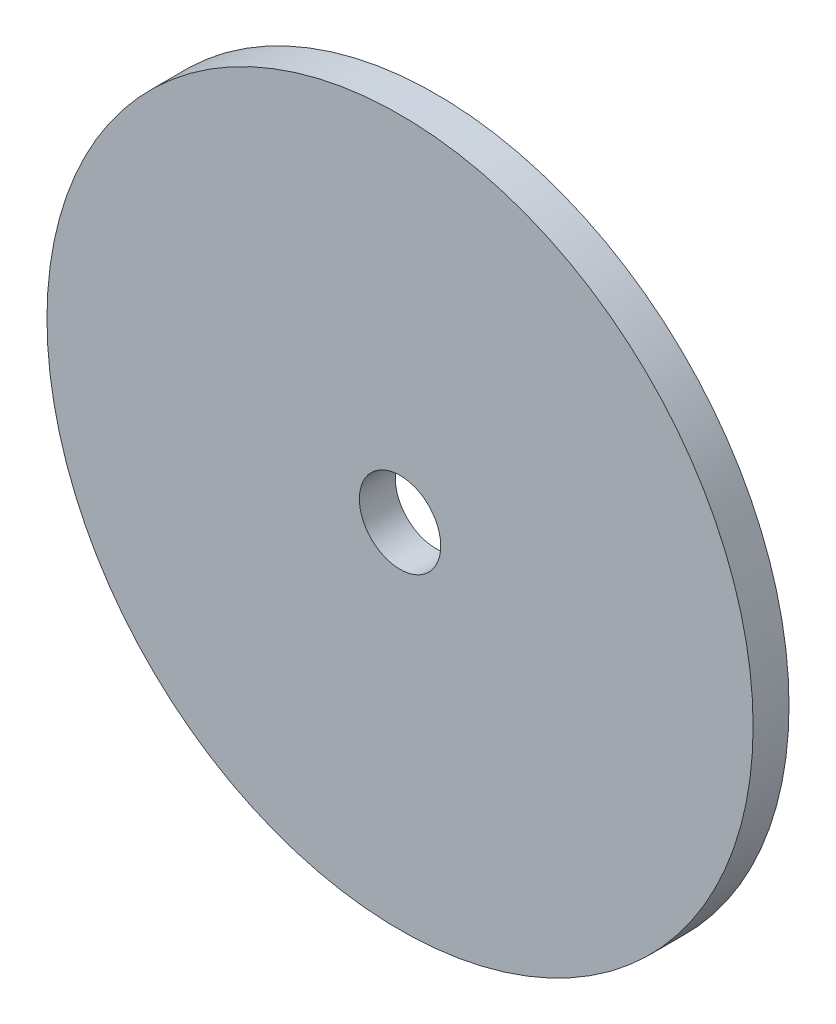
SolidWorks part; units mm, degrees
material "Acrylic (Medium-high impact)"
ref_plane "Front Plane" through (0, 0, 0) normal (0, 0, 1) x (1, 0, 0)
ref_plane "Top Plane" through (0, 0, 0) normal (0, 1, 0) x (1, 0, 0)
ref_plane "Right Plane" through (0, 0, 0) normal (1, 0, 0) x (0, 0, -1)
sketch "Model" plane through (0, 0, 0) normal (0, 0, 1) x (1, 0, 0)
  circle A4 centre (0, 0) radius 3.4
  circle A5 centre (0, 0) radius 29.5
  dimension "D1" = 6.8
  dimension "D2" = 59
extrude "Boss-Extrude1" add sketch "Model" along normal blind 3
equation "\"D2@Model\"=58.80mm+\"cut_free@Parameters@FabricationParameters.sldprt\""
